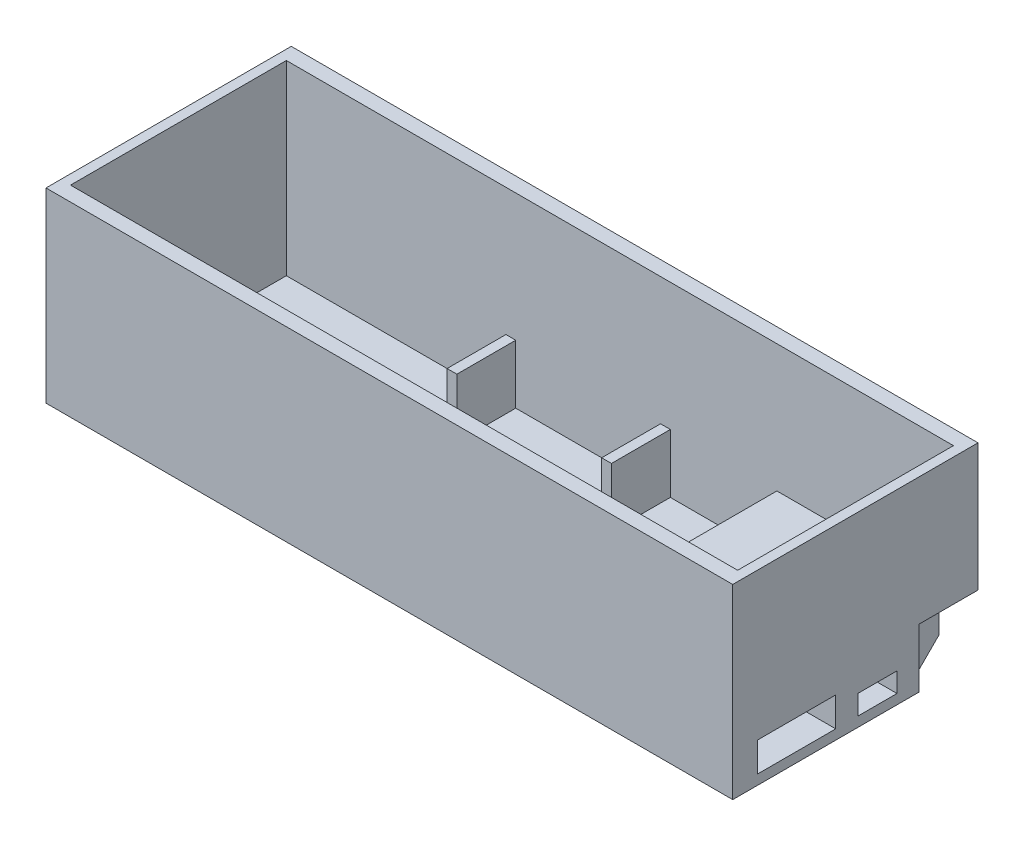
SolidWorks part; units mm, degrees
ref_plane "Plan de face" through (0, 0, 0) normal (0, 0, 1) x (1, 0, 0)
ref_plane "Plan de dessus" through (0, 0, 0) normal (0, 1, 0) x (1, 0, 0)
ref_plane "Plan de droite" through (0, 0, 0) normal (1, 0, 0) x (0, 0, -1)
sketch "Esquisse1" plane through (0, 0, 0) normal (0, 1, 0) x (1, 0, 0)
  line L1 (0, 0) -> (70, 0)
  line L2 (0, 0) -> (0, 25)
  line L3 (0, 25) -> (70, 25)
  line L4 (70, 0) -> (70, 25)
  dimension "D1" = 25
  dimension "D2" = 70
extrude "Boss.-Extru.1" add sketch "Esquisse1" along normal blind 21
sketch "Esquisse2" plane through (0, 21, 0) normal (0, 1, 0) x (1, 0, 0)
  line L0 (0, 0) -> (70, 0) construction
  line L1 (1, 23.5) -> (69, 23.5)
  line L2 (1, 23.5) -> (1, 1.5)
  line L3 (1, 1.5) -> (69, 1.5)
  line L4 (69, 23.5) -> (69, 1.5)
  line L5 (0, 25) -> (0, 0) construction
  dimension "D1" = 22
  dimension "D2" = 1.5
  dimension "D3" = 68
  dimension "D4" = 1
extrude "Enlèv. mat.-Extru.1" cut sketch "Esquisse2" against normal blind 19
sketch "Esquisse3" plane through (0, 2, 0) normal (0, 1, 0) x (1, 0, 0)
  line L0 (69, 23.5) -> (1, 23.5) construction
  line L1 (69, 1.5) -> (51, 1.5)
  line L2 (69, 1.5) -> (69, 23.5)
  line L3 (69, 23.5) -> (51, 23.5)
  line L4 (51, 1.5) -> (51, 23.5)
  line L5 (1, 1.5) -> (69, 1.5) construction
  line L6 (23.3819, 23.5) -> (24.3819, 23.5)
  line L7 (23.3819, 23.5) -> (23.3819, 17.5)
  line L8 (23.3819, 17.5) -> (24.3819, 17.5)
  line L9 (24.3819, 23.5) -> (24.3819, 17.5)
  line L10 (39.1389, 23.5) -> (40.1389, 23.5)
  line L11 (39.1389, 23.5) -> (39.1389, 17.5)
  line L12 (39.1389, 17.5) -> (40.1389, 17.5)
  line L13 (40.1389, 23.5) -> (40.1389, 17.5)
  line L14 (21.9631, 1.5) -> (22.9631, 1.5)
  line L15 (21.9631, 1.5) -> (21.9631, 7.5)
  line L16 (21.9631, 7.5) -> (22.9631, 7.5)
  line L17 (22.9631, 1.5) -> (22.9631, 7.5)
  line L19 (39.1389, 1.5) -> (40.1389, 1.5)
  line L20 (39.1389, 1.5) -> (39.1389, 7.5)
  line L21 (39.1389, 7.5) -> (40.1389, 7.5)
  line L22 (40.1389, 1.5) -> (40.1389, 7.5)
  dimension "D1" = 18
  dimension "D2" = 1
  dimension "D3" = 1
  dimension "D4" = 1
  dimension "D5" = 1
  dimension "D6" = 6
  dimension "D7" = 6
  dimension "D8" = 6
  dimension "D9" = 6
extrude "Boss.-Extru.2" add sketch "Esquisse3" along normal blind 6
sketch "Esquisse4" plane through (70, 0, 0) normal (1, 0, 0) x (0, 0, -1)
  line L0 (25, 21) -> (25, 0) construction
  line L1 (2.5, 6) -> (10.5, 6)
  line L2 (2.5, 6) -> (2.5, 3)
  line L3 (2.5, 3) -> (10.5, 3)
  line L4 (10.5, 6) -> (10.5, 3)
  line L5 (12.743, 5) -> (16.743, 5)
  line L6 (12.743, 5) -> (12.743, 3)
  line L7 (12.743, 3) -> (16.743, 3)
  line L8 (16.743, 5) -> (16.743, 3)
  line L9 (19, 8) -> (25, 8)
  line L10 (19, 8) -> (19, 0)
  line L11 (19, 0) -> (25, 0)
  line L12 (25, 8) -> (25, 0)
  line L13 (0, 21) -> (0, 0) construction
  line L14 (0, 0) -> (25, 0) construction
  dimension "D1" = 8
  dimension "D2" = 3
  dimension "D3" = 4
  dimension "D4" = 2
  dimension "D5" = 8
  dimension "D6" = 6
  dimension "D8" = 2.5
  dimension "D9" = 3
  dimension "D10" = 3
extrude "Enlèv. mat.-Extru.2" cut sketch "Esquisse4" against normal blind 4
chamfer "Chanfrein1" distance 2 angle 45 4 edges at (0, 0, -12.5) (70, 0, -9.5) (33, 0, -25) (35, 0, 0)
